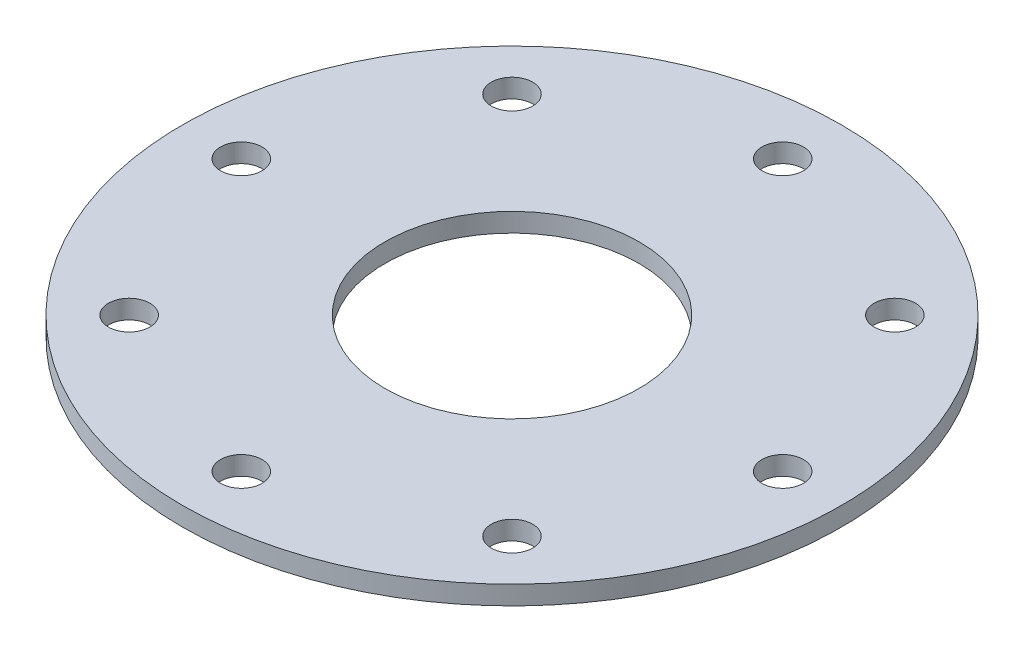
SolidWorks part; units mm, degrees
material "AISI 304"
ref_plane "Спереди" through (0, 0, 0) normal (0, 0, 1) x (1, 0, 0)
ref_plane "Сверху" through (0, 0, 0) normal (0, 1, 0) x (1, 0, 0)
ref_plane "Справа" through (0, 0, 0) normal (1, 0, 0) x (0, 0, -1)
sketch "Эскиз1" plane through (0, 0, 0) normal (0, 1, 0) x (1, 0, 0)
  line L0 (0, 0) -> (70, 0) construction
  circle A0 centre (0, 0) radius 70
  circle A1 centre (0, 0) radius 27
  circle A2 centre (0, 0) radius 57.5 construction
  circle A3 centre (57.5, 0) radius 4.4
  circle A4 centre (40.6586, -40.6586) radius 4.4
  circle A5 centre (0, -57.5) radius 4.4
  circle A6 centre (-40.6586, -40.6586) radius 4.4
  circle A7 centre (-57.5, 0) radius 4.4
  circle A8 centre (-40.6586, 40.6586) radius 4.4
  circle A9 centre (0, 57.5) radius 4.4
  circle A10 centre (40.6586, 40.6586) radius 4.4
  dimension "D1" = 140
  dimension "D2" = 54
  dimension "D3" = 115
  dimension "D4" = 8.8
  dimension "D5" = 8
extrude "Бобышка-Вытянуть1" add sketch "Эскиз1" along normal blind 4
